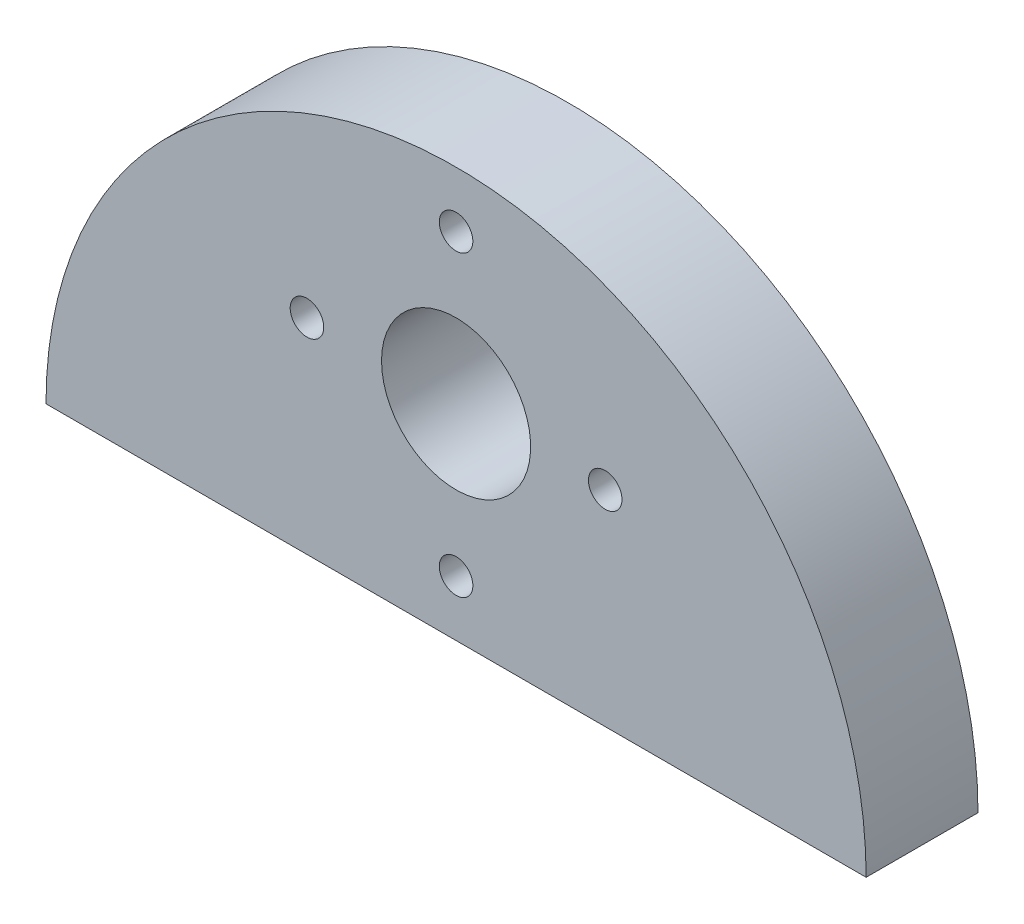
SolidWorks part; units mm, degrees
ref_plane "Plan de face" through (0, 0, 0) normal (0, 0, 1) x (1, 0, 0)
ref_plane "Plan de dessus" through (0, 0, 0) normal (0, 1, 0) x (1, 0, 0)
ref_plane "Plan de droite" through (0, 0, 0) normal (1, 0, 0) x (0, 0, -1)
sketch "Esquisse2" plane through (0, 0, 0) normal (0, 0, 1) x (1, 0, 0)
  line L0 (-22, 0) -> (22, 0)
  line L1 (0, 0) -> (0, 22) construction
  arc A0 (-22, 0) -> (22, 0) centre (0, 0) cw
  dimension "D1" = 22
extrude "Boss.-Extru.2" add sketch "Esquisse2" along normal blind 6 contours A0 L0
sketch "Esquisse4" plane through (0, 0, 0) normal (0, 0, -1) x (-1, 0, 0)
  line L0 (0, 0) -> (0, 22) construction
  line L1 (0, 11) -> (50000, 11) construction
  arc A0 (22, 0) -> (-22, 0) centre (0, 0) ccw construction
  circle A1 centre (0, 11) radius 4
  circle A2 centre (0, 19) radius 0.9
  circle A3 centre (0, 3) radius 0.9
  circle A4 centre (-8, 11) radius 0.9
  circle A5 centre (8, 11) radius 0.9
  dimension "D1" = 1.8
  dimension "D2" = 8
  dimension "D3" = 1.8
  dimension "D4" = 1.8
  dimension "D5" = 8
  dimension "D6" = 8
  dimension "D7" = 8
extrude "Enlèv. mat.-Extru.1" cut sketch "Esquisse4" against normal blind 6
